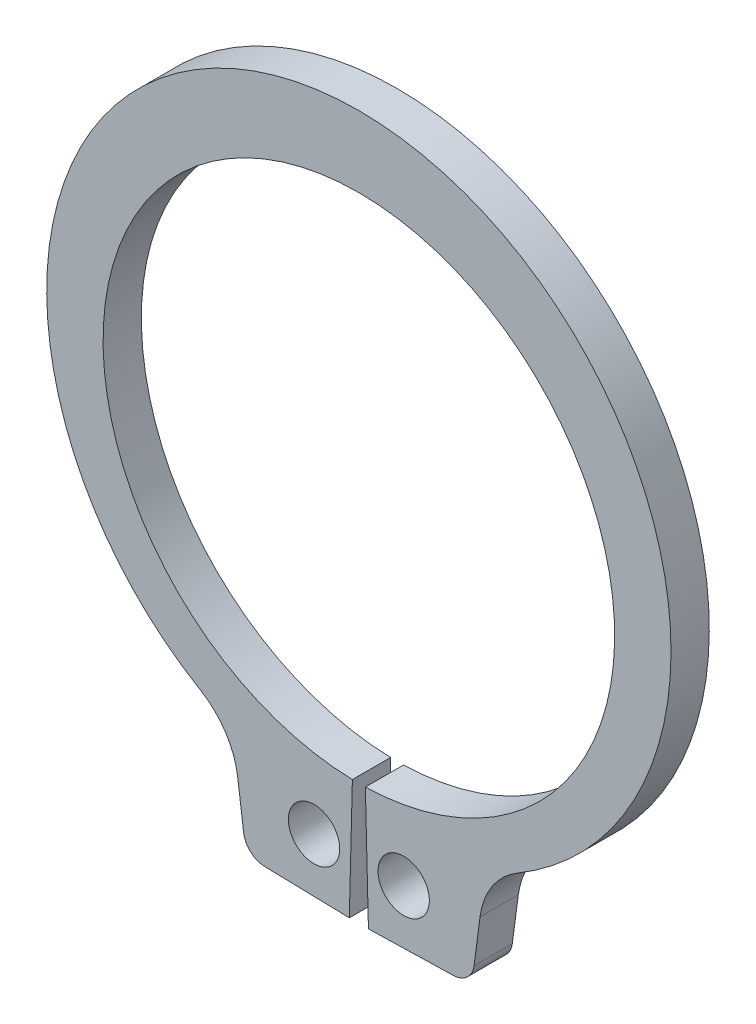
SolidWorks part; units mm, degrees
ref_plane "Plane1" through (0, 0, 0) normal (0, 0, 1) x (1, 0, 0)
ref_plane "Plane2" through (0, 0, 0) normal (0, 1, 0) x (1, 0, 0)
ref_plane "Plane3" through (0, 0, 0) normal (1, 0, 0) x (0, 0, -1)
sketch "Clipboard" plane through (0, 0, 0) normal (0, 0, 1) x (1, 0, 0)
  line L0 (0, 0) -> (1.651, 0)
  line L1 (0, 0) -> (0, 1.016)
  line L2 (0, 0) -> (0, -2.8194)
  circle A0 centre (0, 0) radius 0.5969
  circle A1 centre (0, 0) radius 6.35
  dimension "HoleDia" = 1.1938
  dimension "ShaftDia" = 12.7
  dimension "LargeSection" = 1.651
  dimension "SmallSection" = 1.016
  dimension "LugSection" = 2.8194
sketch "BodySke" plane through (0, 0, 0) normal (0, 0, 1) x (1, 0, 0)
  line L0 (-1.5431, 0) -> (1.5431, 0) construction
  line L1 (0, 0) -> (0, 7.5946) construction
  line L2 (0.1507, -5.9417) -> (0.2223, -8.7602)
  line L3 (-0.1507, -5.9417) -> (-0.2223, -8.7602)
  line L4 (0, 0) -> (4.6029, -7.4568) construction
  line L5 (0, 0) -> (-4.6029, -7.4568) construction
  line L6 (0.2223, -8.7602) -> (2.1935, -8.7102)
  line L7 (2.8153, -7.2215) -> (2.6765, -8.2756)
  line L8 (-2.8153, -7.2215) -> (-2.6765, -8.2756)
  line L9 (-0.2223, -8.7602) -> (-2.1935, -8.7102)
  circle A0 centre (0, 0) radius 5.9436 construction
  arc A1 (0.1507, -5.9417) -> (-0.1507, -5.9417) centre (0, 0) ccw
  arc A2 (3.6556, -5.9222) -> (-3.6556, -5.9222) centre (0, 0.3419) ccw construction
  arc A3 (0.2223, -8.7602) -> (2.1944, -8.4838) centre (0, 0) ccw construction
  arc A4 (3.6864, -5.9041) -> (2.8153, -7.2215) centre (4.6029, -7.4568) ccw
  arc A5 (-2.8153, -7.2215) -> (-3.6864, -5.9041) centre (-4.6029, -7.4568) ccw
  arc A6 (-2.1944, -8.4838) -> (-0.2223, -8.7602) centre (0, 0) ccw construction
  arc A7 (3.6864, -5.9041) -> (-3.6864, -5.9041) centre (0, 0.3419) ccw
  arc A8 (-2.8444, -7.0007) -> (2.8444, -7.0007) centre (0, 0) ccw construction
  circle A9 centre (1.0414, -7.4844) radius 0.5969
  circle A10 centre (-1.0414, -7.4844) radius 0.5969
  arc A11 (2.6765, -8.2756) -> (2.1935, -8.7102) centre (2.1808, -8.2103) cw
  arc A12 (-2.6765, -8.2756) -> (-2.1935, -8.7102) centre (-2.1808, -8.2103) ccw
  point P28 (2.6671, -8.3473)
  point P31 (-2.6671, -8.3473)
  dimension "GrooveDia" = 11.8872
  dimension "D3" = 0.5
  dimension "LugRad" = 8.763
  dimension "HoleOffsetRad" = 7.5565
  dimension "HoleDia" = 1.1938
  dimension "D2" = 15
  dimension "LargeRad" = 7.5946
  dimension "SmallRad" = 6.9596
  dimension "Gap" = 0.4445
  dimension "SmallAngle" = 63.371
  dimension "HoleSpacing" = 2.0828
extrude "Body" add sketch "BodySke" against normal blind 0.889
equation "' \"ShaftDia@Clipboard\" = 4"
equation "' \"Thickness@Body\" = 0.25"
equation "' \"GrooveDia@BodySke\" = 3.8"
equation "' \"LugSection@Clipboard\" = 1.35"
equation "' \"LargeSection@Clipboard\" = 0.65"
equation "' \"SmallSection@Clipboard\" = 0.4"
equation "' \"HoleDia@Clipboard\" = 0.6"
equation "' \"ShaftDia@Clipboard\" = 15"
equation "' \"Thickness@Body\" = 0.9"
equation "' \"GrooveDia@BodySke\" = 14.15"
equation "' \"LugSection@Clipboard\" = 2.8"
equation "' \"LargeSection@Clipboard\" = 1.8"
equation "' \"SmallSection@Clipboard\" = 1.05"
equation "' \"HoleDia@Clipboard\" = 1.2"
equation "\"Gap@BodySke\" =  \"Thickness@Body\" / 2"
equation "\"LargeRad@BodySke\" =  \"GrooveDia@BodySke\" / 2 +  \"LargeSection@Clipboard\""
equation "\"SmallRad@BodySke\" =  \"GrooveDia@BodySke\" / 2 +  \"SmallSection@Clipboard\""
equation "\"LugRad@BodySke\" = \"GrooveDia@BodySke\" / 2 + \"LugSection@Clipboard\""
equation "\"HoleOffsetRad@BodySke\" = (  \"ShaftDia@Clipboard\" / 2 + \"LugRad@BodySke\" ) / 2"
equation "\"HoleSpacing@BodySke\" = \"Gap@BodySke\"  * 2 +  \"HoleDia@Clipboard\""
equation "\"HoleDia@BodySke\" =  \"HoleDia@Clipboard\""
equation "\"SmallAngle@BodySke\" = atn(\"HoleSpacing@BodySke\" / 2 / sqr(\"HoleOffsetRad@BodySke\"  * \"HoleOffsetRad@BodySke\" - (\"HoleSpacing@BodySke\" / 2) * (\"HoleSpacing@BodySke\" / 2) ))  * 8 * ( 180 / 3.141593)"
